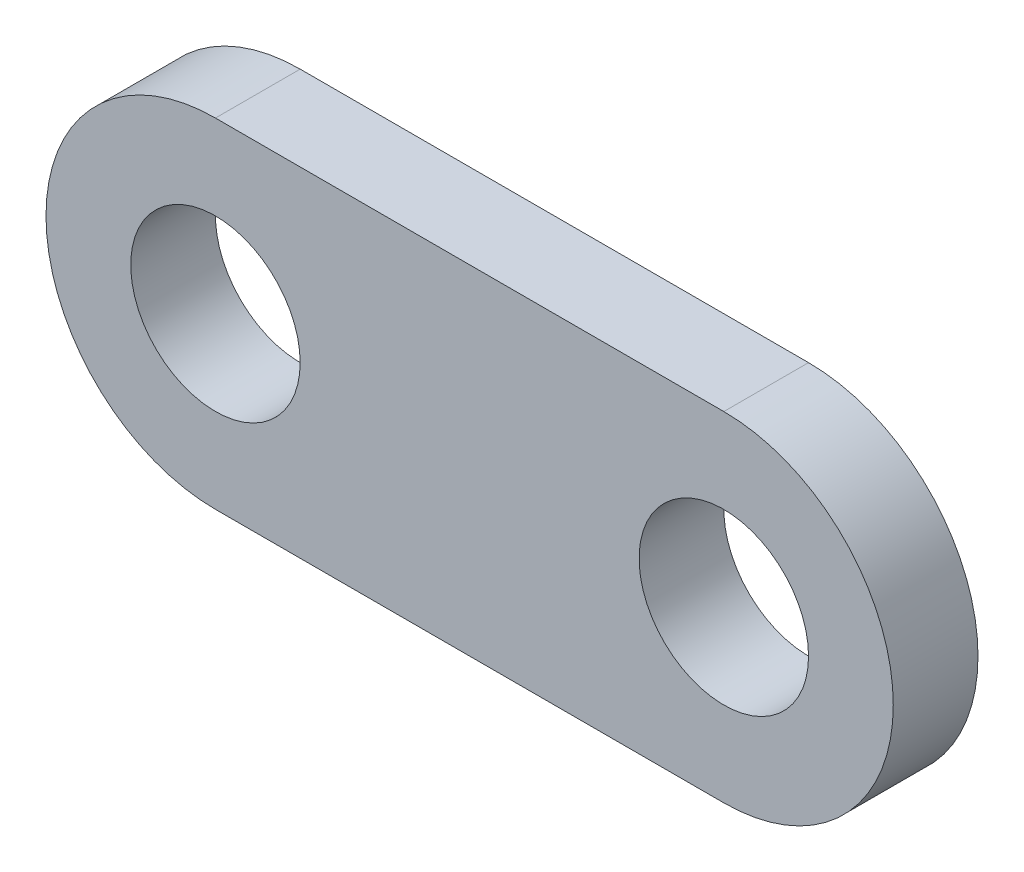
SolidWorks part; units mm, degrees
ref_plane "Plano frontal" through (0, 0, 0) normal (0, 0, 1) x (1, 0, 0)
ref_plane "Plano superior" through (0, 0, 0) normal (0, 1, 0) x (1, 0, 0)
ref_plane "Plano direito" through (0, 0, 0) normal (1, 0, 0) x (0, 0, -1)
sketch "Esboço1" plane through (0, 0, 0) normal (0, 0, 1) x (1, 0, 0)
  line L1 (0, 10) -> (30, 10)
  line L2 (0, 5) -> (0, -5)
  line L3 (0, -10) -> (30, -10)
  line L4 (30, 5) -> (30, -5)
  arc A0 (0, 10) -> (0, -10) centre (0, 0) ccw
  circle A1 centre (30, 0) radius 5
  circle A2 centre (0, 0) radius 5
  arc A3 (30, -10) -> (30, 10) centre (30, 0) ccw
  dimension "D1" = 20
  dimension "D2" = 10
  dimension "D3" = 30
extrude "Ressalto-extrusão1" add sketch "Esboço1" along normal blind 5 contours L3 A3 L1 A0 A1 A2
